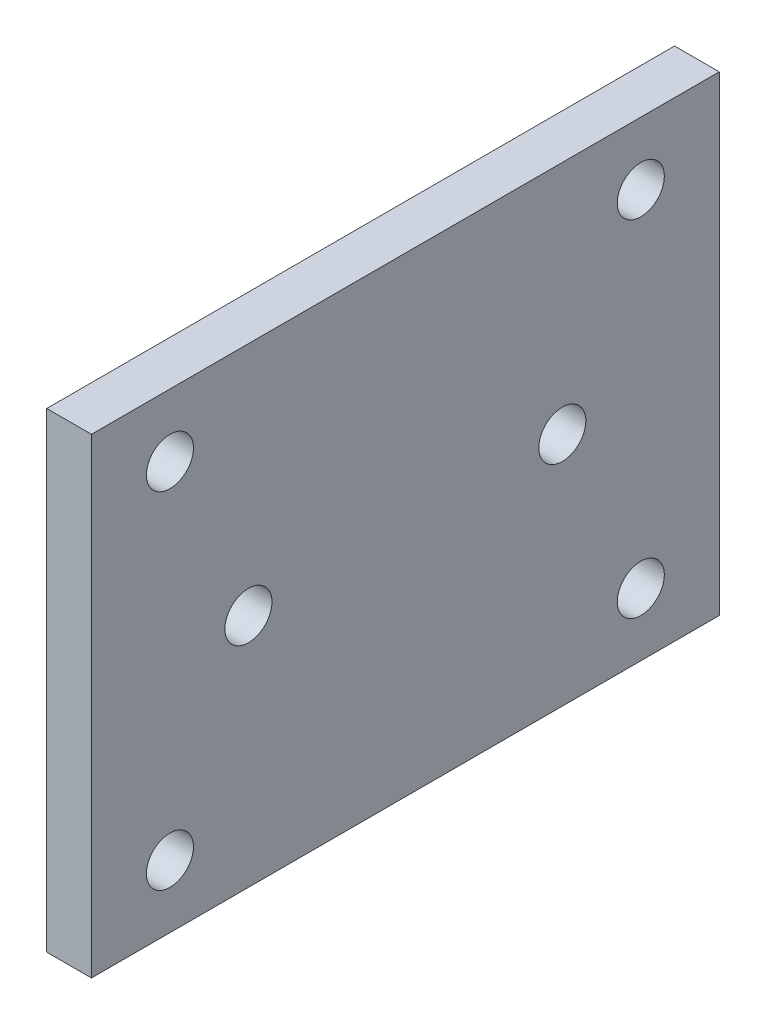
SolidWorks part; units mm, degrees
ref_plane "Front" through (0, 0, 0) normal (0, 0, 1) x (1, 0, 0)
ref_plane "Top" through (0, 0, 0) normal (0, 1, 0) x (1, 0, 0)
ref_plane "Right" through (0, 0, 0) normal (1, 0, 0) x (0, 0, -1)
sketch "Sketch1" plane through (0, 0, 0) normal (1, 0, 0) x (0, 0, -1)
  line L1 (-20, 15) -> (20, 15)
  line L2 (-20, 15) -> (-20, -15)
  line L3 (-20, -15) -> (20, -15)
  line L4 (20, 15) -> (20, -15)
  line L5 (-20, 15) -> (20, -15) construction
  line L6 (-20, -15) -> (20, 15) construction
  point P0 (0, 0)
  dimension "D1" = 40
  dimension "D2" = 30
extrude "Boss-Extrude1" add sketch "Sketch1" along normal blind 2.85
sketch "Sketch2" plane through (2.85, 0, 0) normal (1, 0, 0) x (0, 0, -1)
  line L0 (-10, 0) -> (10, 0) construction
  circle A0 centre (-10, 0) radius 1.5
  circle A1 centre (10, 0) radius 1.5
  dimension "D1" = 3
  dimension "D3" = 20
extrude "Cut-Extrude1" cut sketch "Sketch2" against normal through all
sketch "Sketch3" plane through (2.85, 0, 0) normal (1, 0, 0) x (0, 0, -1)
  line L0 (-15, 11) -> (15, 11) construction
  line L1 (0, 0) -> (0, 11) construction
  line L2 (20, -15) -> (20, 15) construction
  line L3 (20, 15) -> (-20, 15) construction
  circle A0 centre (-15, 11) radius 1.5
  circle A1 centre (15, 11) radius 1.5
  dimension "D1" = 3
  dimension "D2" = 5
  dimension "D3" = 4
extrude "Cut-Extrude2" cut sketch "Sketch3" against normal through all
mirror "Mirror1" about plane through (0, 0, 0) normal (0, 1, 0) of "Cut-Extrude2"
